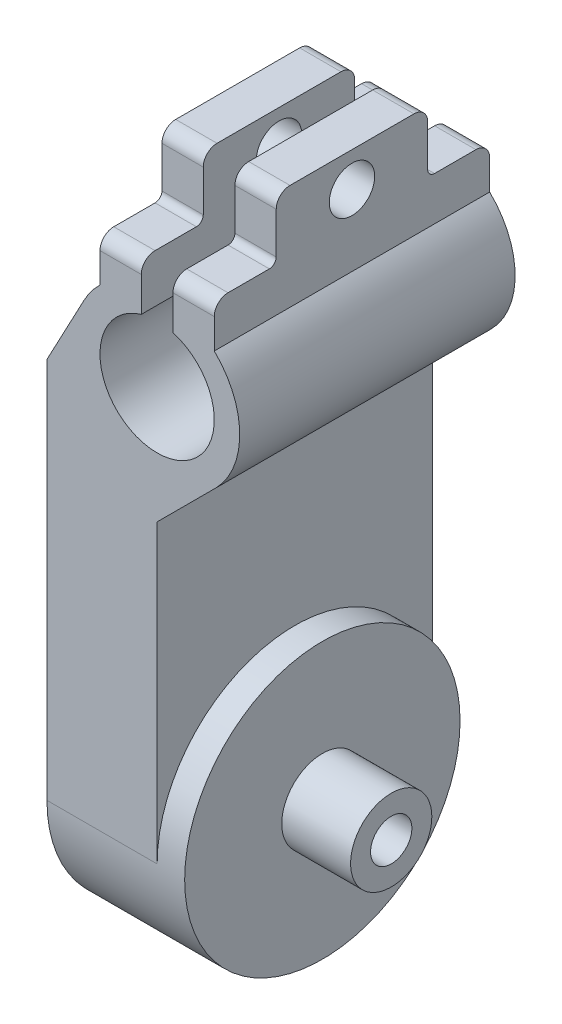
SolidWorks part; units mm, degrees
ref_plane "前视基准面" through (0, 0, 0) normal (0, 0, 1) x (1, 0, 0)
ref_plane "上视基准面" through (0, 0, 0) normal (0, 1, 0) x (1, 0, 0)
ref_plane "右视基准面" through (0, 0, 0) normal (1, 0, 0) x (0, 0, -1)
other "Configuration Table"
sketch "草图1" plane through (0, 0, 0) normal (0, 0, 1) x (1, 0, 0)
  line L0 (-1.15, 3.9875) -> (-1.15, 12)
  line L1 (0, 0) -> (0, 9.969) construction
  line L2 (-1.15, 12) -> (-4.15, 12)
  line L3 (-4.15, 12) -> (-4.15, 4.3333)
  line L4 (4.15, 12) -> (4.15, 4.3333)
  line L5 (1.15, 12) -> (4.15, 12)
  line L6 (1.15, 3.9875) -> (1.15, 12)
  line L7 (-8, -2.2655) -> (-5.2977, 2.8168)
  line L8 (-8, -2.2655) -> (-8, -30)
  line L9 (4.2426, -4.2426) -> (0, -8.4853)
  line L10 (0, -8.4853) -> (0, -30)
  line L11 (-8, -30) -> (0, -30)
  arc A0 (-1.15, 3.9875) -> (1.15, 3.9875) centre (0, 0) ccw
  arc A1 (-4.15, 4.3333) -> (-5.2977, 2.8168) centre (0, 0) ccw
  arc A2 (4.2426, -4.2426) -> (4.15, 4.3333) centre (0, 0) ccw
  dimension "D1" = 8.3
  dimension "D4" = 12
  dimension "D2" = 2.3
  dimension "D3" = 12
  dimension "D5" = 3
  dimension "D6" = 30
  dimension "D7" = 152
  dimension "D8" = 8
  dimension "D9" = 135
extrude "凸台-拉伸1" add sketch "草图1" along normal mid plane 20
sketch "草图2" plane through (0, 0, 0) normal (1, 0, 0) x (0, 0, -1)
  line L0 (-10, -30) -> (10, -30) construction
  circle A0 centre (0, -30) radius 10
extrude "凸台-拉伸2" add sketch "草图2" against normal up to surface and the other way blind 2 up to face at (-8, -16.1327, 0)
sketch "草图4" plane through (2, 0, 0) normal (1, 0, 0) x (0, 0, -1)
  circle A0 centre (0, -30) radius 2.95
  dimension "D1" = 5.9
extrude "凸台-拉伸3" add sketch "草图4" along normal blind 5
sketch "草图5" plane through (7, 0, 0) normal (1, 0, 0) x (0, 0, -1)
  circle A0 centre (0, -30) radius 1.5
  dimension "D1" = 3
extrude "切除-拉伸1" cut sketch "草图5" against normal through all
sketch "草图6" plane through (4.15, 0, 0) normal (1, 0, 0) x (0, 0, -1)
  line L0 (0, 0) -> (0, 16.5087) construction
  line L1 (-10, 12) -> (10, 12) construction
  line L2 (-5.5, 7.5) -> (-20.2045, 7.5)
  line L3 (-5.5, 7.5) -> (-5.5, 16.0204)
  line L4 (-5.5, 16.0204) -> (-20.2045, 16.0204)
  line L5 (-20.2045, 7.5) -> (-20.2045, 16.0204)
  line L6 (20.2045, 7.5) -> (20.2045, 16.0204)
  line L7 (5.5, 16.0204) -> (20.2045, 16.0204)
  line L8 (5.5, 7.5) -> (5.5, 16.0204)
  line L9 (5.5, 7.5) -> (20.2045, 7.5)
  circle A0 centre (0, 9.5) radius 1.65
  dimension "D3" = 3.3
  dimension "D1" = 11
  dimension "D2" = 4.5
  dimension "D4" = 2.5
extrude "切除-拉伸2" cut sketch "草图6" against normal through all
fillet "圆角1" radius 1 8 edges at (2.65, 7.5, -10) (-2.65, 7.5, -10) (-2.65, 7.5, 10) (2.65, 7.5, 10) (-2.65, 12, 5.5) (2.65, 12, -5.5) (-2.65, 12, -5.5) (2.65, 12, 5.5)
fillet "圆角2" radius 0.5 4 edges at (2.65, 7.5, -5.5) (-2.65, 7.5, -5.5) (2.65, 7.5, 5.5) (-2.65, 7.5, 5.5)
